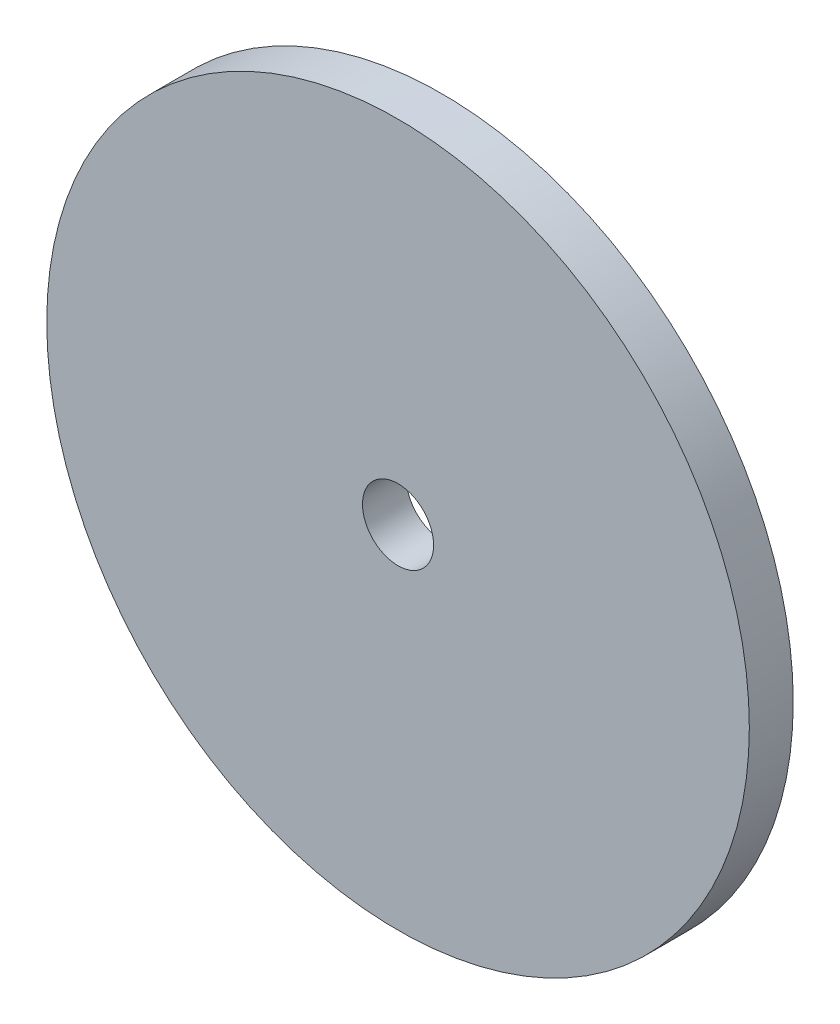
SolidWorks part; units mm, degrees
material "Balsa"
ref_plane "Front Plane" through (0, 0, 0) normal (0, 0, 1) x (1, 0, 0)
ref_plane "Top Plane" through (0, 0, 0) normal (0, 1, 0) x (1, 0, 0)
ref_plane "Right Plane" through (0, 0, 0) normal (1, 0, 0) x (0, 0, -1)
sketch "Sketch1" plane through (0, 0, 0) normal (0, 0, 1) x (1, 0, 0)
  circle A1 centre (0, 0) radius 40
  circle A2 centre (0, 0) radius 4.05
  dimension "D1" = 80
  dimension "D2" = 8.1
extrude "Boss-Extrude1" add sketch "Sketch1" along normal blind 5
